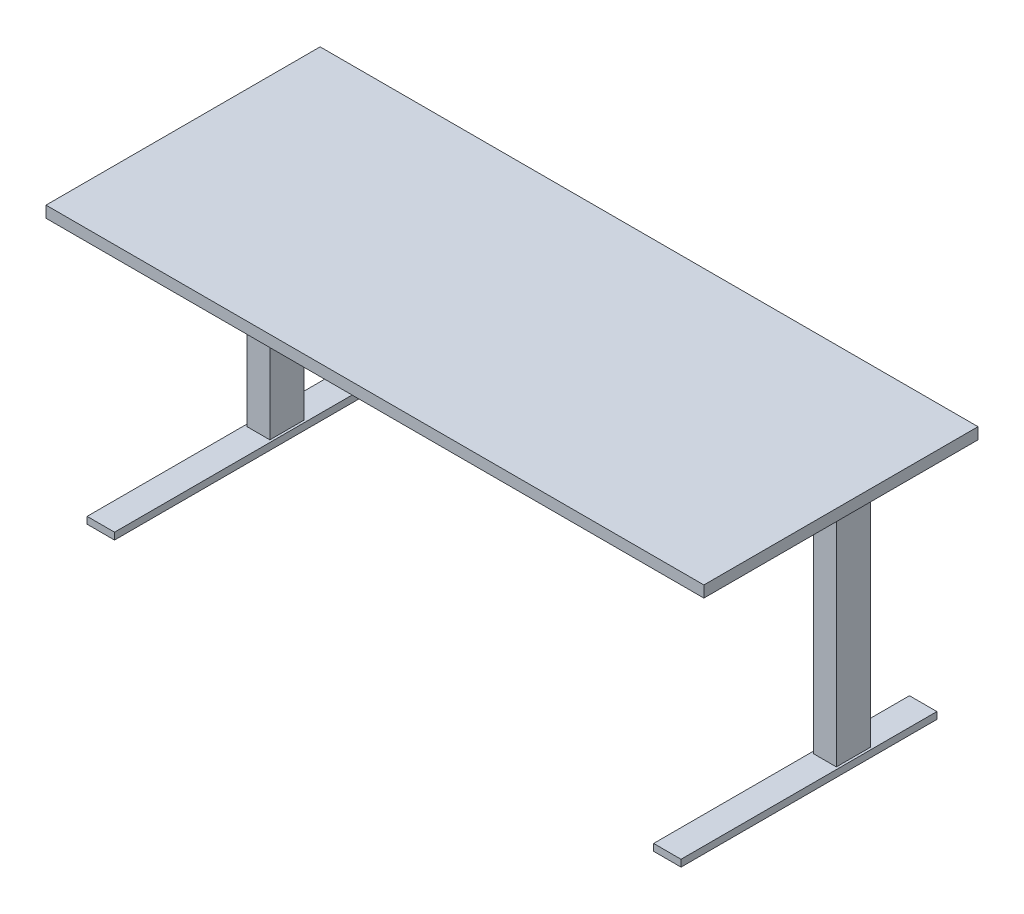
SolidWorks part; units mm, degrees
material "Plain Carbon Steel"
ref_plane "Front Plane" through (0, 0, 0) normal (0, 0, 1) x (1, 0, 0)
ref_plane "Top Plane" through (0, 0, 0) normal (0, 1, 0) x (1, 0, 0)
ref_plane "Right Plane" through (0, 0, 0) normal (1, 0, 0) x (0, 0, -1)
sketch "Sketch1" plane through (0, 0, 0) normal (0, 1, 0) x (1, 0, 0)
  line L1 (-914.4, -381) -> (914.4, -381)
  line L2 (-914.4, -381) -> (-914.4, 381)
  line L3 (-914.4, 381) -> (914.4, 381)
  line L4 (914.4, -381) -> (914.4, 381)
  line L5 (-914.4, -381) -> (914.4, 381) construction
  line L6 (-914.4, 381) -> (914.4, -381) construction
  point P0 (0, 0)
  dimension "D1" = 762
  dimension "D2" = 1828.8
extrude "Boss-Extrude1" add sketch "Sketch1" against normal blind 31.75
sketch "Sketch2" plane through (0, -31.75, 0) normal (0, -1, 0) x (1, 0, 0)
  line L0 (914.4, -381) -> (-914.4, -381) construction
  line L1 (-850.9, -279.4) -> (-819.15, -279.4)
  line L2 (-850.9, -279.4) -> (-850.9, -38.1)
  line L3 (-850.9, -38.1) -> (-819.15, -38.1)
  line L4 (-819.15, -279.4) -> (-819.15, -38.1)
  line L5 (-914.4, -381) -> (-914.4, 381) construction
  dimension "D1" = 101.6
  dimension "D2" = 241.3
  dimension "D3" = 31.75
  dimension "D4" = 63.5
extrude "Boss-Extrude2" add sketch "Sketch2" along normal blind 50.8
sketch "Sketch3" plane through (0, -31.75, 0) normal (0, -1, 0) x (1, 0, 0)
  line L0 (914.4, -381) -> (-914.4, -381) construction
  line L1 (-819.15, -177.8) -> (-755.65, -177.8)
  line L2 (-819.15, -177.8) -> (-819.15, -82.55)
  line L3 (-819.15, -82.55) -> (-755.65, -82.55)
  line L4 (-755.65, -177.8) -> (-755.65, -82.55)
  line L5 (-819.15, -279.4) -> (-819.15, -38.1) construction
  dimension "D1" = 203.2
  dimension "D2" = 95.25
  dimension "D3" = 63.5
extrude "Boss-Extrude3" add sketch "Sketch3" along normal blind 685.8
sketch "Sketch4" plane through (0, -717.55, 0) normal (0, -1, 0) x (1, 0, 0)
  line L0 (-755.65, -82.55) -> (-819.15, -82.55) construction
  line L1 (-825.5, -355.6) -> (-749.3, -355.6)
  line L2 (-825.5, -355.6) -> (-825.5, 355.6)
  line L3 (-825.5, 355.6) -> (-749.3, 355.6)
  line L4 (-749.3, -355.6) -> (-749.3, 355.6)
  line L5 (-825.5, -355.6) -> (-749.3, 355.6) construction
  line L6 (-825.5, 355.6) -> (-749.3, -355.6) construction
  point P0 (-787.4, 0)
  point P7 (-787.4, -82.55)
  point P8 (0, 0)
  dimension "D1" = 76.2
  dimension "D2" = 711.2
extrude "Boss-Extrude4" add sketch "Sketch4" along normal offset from surface (19.05 mm away) 736.6 up to face at (0, 0, 0)
mirror "Mirror1" about plane through (0, 0, 0) normal (1, 0, 0) of "Boss-Extrude4", "Boss-Extrude3", "Boss-Extrude2"
